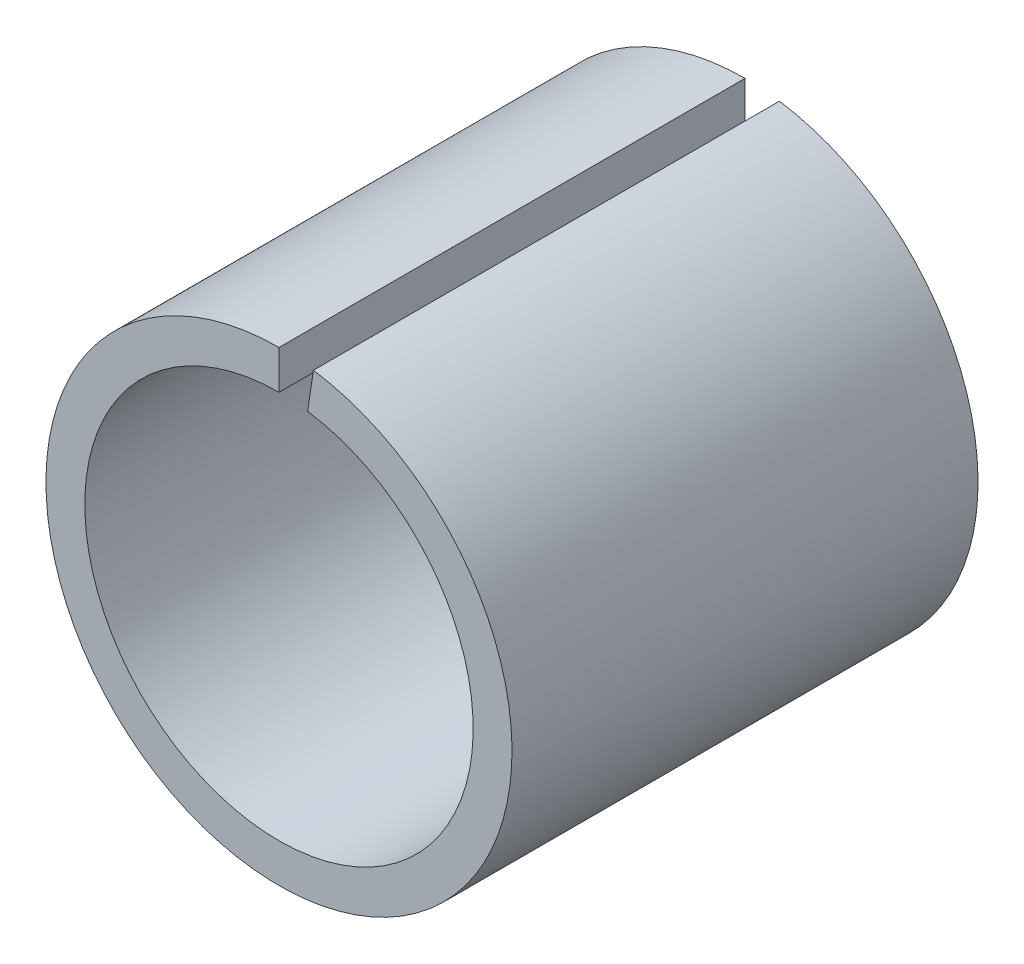
SolidWorks part; units mm, degrees
ref_plane "前视基准面" through (0, 0, 0) normal (0, 0, 1) x (1, 0, 0)
ref_plane "上视基准面" through (0, 0, 0) normal (0, 1, 0) x (1, 0, 0)
ref_plane "右视基准面" through (0, 0, 0) normal (1, 0, 0) x (0, 0, -1)
sketch "草图1" plane through (0, 0, 0) normal (0, 0, 1) x (1, 0, 0)
  circle A0 centre (0, 0) radius 6
  circle A1 centre (0, 0) radius 5
  dimension "D1" = 10
  dimension "D2" = 12
extrude "凸台-拉伸1" add sketch "草图1" along normal blind 12
sketch "草图2" plane through (0, 0, 12) normal (0, 0, 1) x (1, 0, 0)
  line L0 (0, 0) -> (0, 6)
  line L1 (0, 6) -> (1.7209, 11.5336)
  line L2 (1.7209, 11.5336) -> (0, 0)
  circle A0 centre (0, 0) radius 6 construction
extrude "切除-拉伸1" cut sketch "草图2" against normal blind 20
